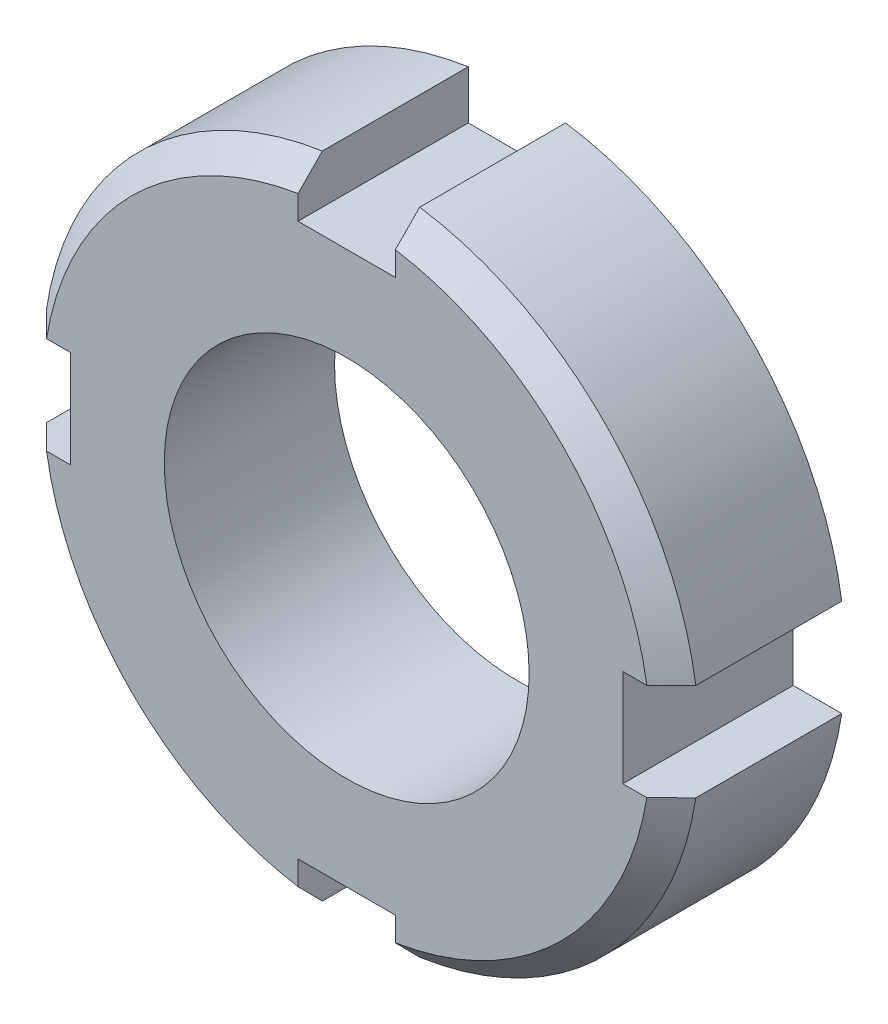
SolidWorks part; units mm, degrees
material "AISI 1020"
ref_plane "Front Plane" through (0, 0, 0) normal (0, 0, 1) x (1, 0, 0)
ref_plane "Top Plane" through (0, 0, 0) normal (0, 1, 0) x (1, 0, 0)
ref_plane "Right Plane" through (0, 0, 0) normal (1, 0, 0) x (0, 0, -1)
sketch "Sketch2" plane through (0, 0, 0) normal (0, 0, 1) x (1, 0, 0)
  circle A0 centre (0, 0) radius 13.5
  dimension "D1" = 27
extrude "Boss-Extrude2" add sketch "Sketch2" along normal blind 7
sketch "Sketch4" plane through (0, 0, 7) normal (0, 0, 1) x (1, 0, 0)
  line L0 (0, 15.8974) -> (0, -18.3368) construction
  line L1 (-2, 13.351) -> (-2, 11.351)
  line L2 (-2, 11.351) -> (2, 11.351)
  line L3 (2, 11.351) -> (2, 13.351)
  line L4 (13.351, 2) -> (11.351, 2)
  line L5 (11.351, 2) -> (11.351, -2)
  line L6 (11.351, -2) -> (13.351, -2)
  line L7 (2, -13.351) -> (2, -11.351)
  line L8 (2, -11.351) -> (-2, -11.351)
  line L9 (-2, -11.351) -> (-2, -13.351)
  line L10 (-13.351, -2) -> (-11.351, -2)
  line L11 (-11.351, -2) -> (-11.351, 2)
  line L12 (-11.351, 2) -> (-13.351, 2)
  circle A0 centre (0, 0) radius 13.5 construction
  arc A1 (-2, 13.351) -> (2, 13.351) centre (0, 0) cw
  arc A2 (13.351, 2) -> (13.351, -2) centre (0, 0) cw
  arc A3 (2, -13.351) -> (-2, -13.351) centre (0, 0) cw
  arc A4 (-13.351, -2) -> (-13.351, 2) centre (0, 0) cw
  point P6 (0, 11.351)
  point P26 (0, 0)
  point P33 (0, 0)
  dimension "D1" = 2
  dimension "D2" = 2
  dimension "D3" = 4
  dimension "D4" = 4
extrude "Cut-Extrude1" cut sketch "Sketch4" against normal through all
sketch "Sketch5" plane through (0, 0, 7) normal (0, 0, 1) x (1, 0, 0)
  circle A0 centre (0, 0) radius 7.5
  dimension "D1" = 15
extrude "Cut-Extrude2" cut sketch "Sketch5" against normal through all
cosmetic thread "Cosmetic Thread1" parameters "D2"=18
chamfer "Chamfer1" distance 1 angle 45 4 edges at (9.5459, -9.5459, 7) (-9.5459, -9.5459, 7) (-9.5459, 9.5459, 7) (9.5459, 9.5459, 7)
